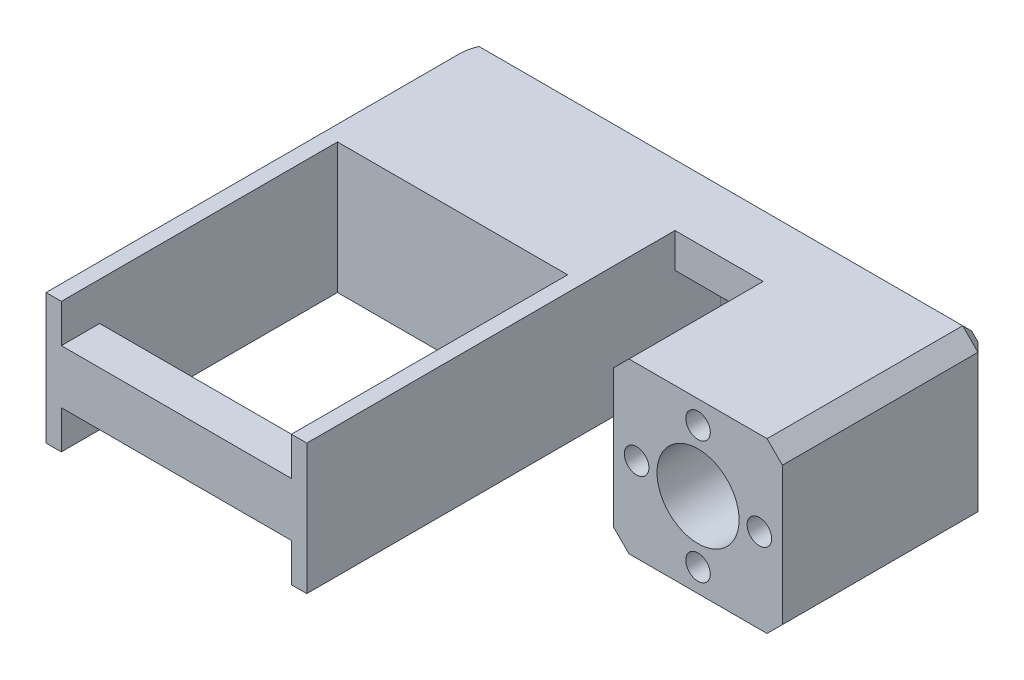
SolidWorks part; units mm, degrees
ref_plane "Płaszczyzna przednia" through (0, 0, 0) normal (0, 0, 1) x (1, 0, 0)
ref_plane "Płaszczyzna górna" through (0, 0, 0) normal (0, 1, 0) x (1, 0, 0)
ref_plane "Płaszczyzna prawa" through (0, 0, 0) normal (1, 0, 0) x (0, 0, -1)
sketch "Szkic2" plane through (0, 0, 0) normal (0, 1, 0) x (1, 0, 0)
  line L0 (0, 0) -> (0, 11.0602) construction
  line L5 (17, 19) -> (-17, 19)
  line L6 (17, 19) -> (17, -19)
  line L11 (17, -19) -> (-17, -19)
  line L12 (-17, 19) -> (-17, -19)
  line L13 (17, 19) -> (-17, -19) construction
  line L14 (17, -19) -> (-17, 19) construction
  line L16 (15, 17) -> (-15, 17)
  line L17 (15, 17) -> (15, -14)
  line L18 (15, -14) -> (-15, -14)
  line L19 (-15, 17) -> (-15, -14)
  line L20 (15, 17) -> (-15, -14) construction
  line L21 (15, -14) -> (-15, 17) construction
  point P0 (0, 0)
  point P5 (0, 1.5)
  dimension "D1" = 34
  dimension "D2" = 38
  dimension "D3" = 2
  dimension "D4" = 2
  dimension "D5" = 5
extrude "Dodanie-wyciągnięcie1" add sketch "Szkic2" along normal blind 17
sketch "Szkic6" plane through (0, 0, 14) normal (0, 0, -1) x (-1, 0, 0)
  line L0 (0, 17) -> (0, 0) construction
  line L1 (15, 17) -> (-15, 17) construction
  line L2 (15, 0) -> (-15, 0) construction
  line L3 (-15, 17) -> (-15, 0) construction
  line L4 (15, 5) -> (-15, 5)
  line L5 (15, 5) -> (15, 12)
  line L6 (15, 12) -> (-15, 12)
  line L7 (-15, 5) -> (-15, 12)
  line L8 (15, 5) -> (-15, 12) construction
  line L9 (15, 12) -> (-15, 5) construction
  line L11 (-15, 17) -> (15, 17)
  line L12 (-15, 17) -> (-15, 0)
  line L13 (-15, 0) -> (15, 0)
  line L14 (15, 17) -> (15, 0)
  point P6 (0, 8.5)
  line M9 (-15, 0) -> (15, 0)
  line M10 (15, 0) -> (15, 17)
  line M11 (15, 17) -> (-15, 17)
  line M12 (-15, 17) -> (-15, 0)
  dimension "D1" = 5
extrude "Wytnij-wyciągnięcie1" cut sketch "Szkic6" against normal blind 17 contours L6 M10 M11 M12 | L4 M10 M12 M9
sketch "Szkic7" plane through (0, 0, -19) normal (0, 0, -1) x (-1, 0, 0)
  line L1 (-17, 17) -> (17, 17)
  line L2 (-17, 17) -> (-17, 0)
  line L3 (-17, 0) -> (17, 0)
  line L4 (17, 17) -> (17, 0)
extrude "Dodanie-wyciągnięcie2" add sketch "Szkic7" along normal blind 10
sketch "Szkic8" plane through (0, 0, -29) normal (0, 0, -1) x (-1, 0, 0)
  line L0 (-17, 17) -> (-17, 18) construction
  line L1 (-17, 17) -> (-24, 17)
  line L2 (-17, 17) -> (-17, 12.5)
  line L3 (-17, 12.5) -> (-24, 12.5)
  line L4 (-24, 17) -> (-24, 12.5)
  line L5 (-17, 17) -> (17, 17)
  line L6 (-17, 17) -> (-17, 0)
  line L7 (-17, 0) -> (17, 0)
  line L8 (17, 17) -> (17, 0)
  line L9 (-17, 18) -> (-22.5, 18) construction
  line L10 (-37.5, 18) -> (-37.5, -6) construction
  line L11 (-22.5, 18) -> (-52.5, 18) construction
  line L12 (-24, 17) -> (-37.5, 17)
  line L13 (-24, 12.5) -> (-26.9837, 2.7739)
  circle A0 centre (-37.5, 6) radius 5.35
  circle A1 centre (-37.5, 6) radius 11
  line M16 (-17, 17) -> (-17, 0)
  line M17 (-17, 0) -> (17, 0)
  line M18 (17, 0) -> (17, 17)
  line M19 (17, 17) -> (-17, 17)
  dimension "D6" = 10.7
  dimension "D1" = 4.5
  dimension "D2" = 7
  dimension "D3" = 5.5
  dimension "D4" = 1
  dimension "D5" = 24
  dimension "30" = 30
extrude "Dodanie-wyciągnięcie3" add sketch "Szkic8" along normal blind 10 contours A1 A0 | A1 L13 L4 L12 | L1 L4 L3 M16 | M19 M16 M17 M18
sketch "Szkic10" plane through (0, 0, -29) normal (0, 0, 1) x (1, 0, 0)
  circle A0 centre (37.5, 6) radius 5.35
  circle A1 centre (37.5, 6) radius 11
extrude "Dodanie-wyciągnięcie4" add sketch "Szkic10" along normal blind 17.5
sketch "Szkic11" plane through (0, 0, -39) normal (0, 0, -1) x (-1, 0, 0)
  circle A0 centre (-37.5, 6) radius 4.2
  circle A1 centre (-37.5, 6) radius 5.35
  dimension "D1" = 8.4
extrude "Dodanie-wyciągnięcie5" add sketch "Szkic11" against normal blind 16
sketch "Szkic13" plane through (0, 0, -11.5) normal (0, 0, 1) x (1, 0, 0)
  line L0 (37.5, 6) -> (37.5, 14) construction
  circle A0 centre (37.5, 6) radius 8
  circle A1 centre (37.5, 14) radius 1.6
  circle A2 centre (45.5, 6) radius 1.6
  circle A3 centre (37.5, -2) radius 1.6
  circle A4 centre (29.5, 6) radius 1.6
  point P16 (37.5, 6)
  dimension "D3" = 3.2
  dimension "D1" = 8
  dimension "D2" = 4
extrude "Wytnij-wyciągnięcie2" cut sketch "Szkic13" against normal blind 10 contours A0 A4 | A0 A4 | A1 L0 A0 | A0 A1 | L0 A1 A0 | A0 A2 | A0 A2 | A0 A3 | A0 A3
sketch "Szkic16" plane through (0, 0, -39) normal (0, 0, -1) x (-1, 0, 0)
  line L0 (17, 17) -> (-37.5, 17) construction
  line L1 (-26.5, 17) -> (-48.5, 17)
  line L2 (-26.5, 17) -> (-26.5, -5)
  line L3 (-26.5, -5) -> (-48.5, -5)
  line L4 (-48.5, 17) -> (-48.5, -5)
  line L5 (-26.5, 17) -> (-48.5, -5) construction
  line L6 (-26.5, -5) -> (-48.5, 17) construction
  arc A0 (-37.5, 17) -> (-26.9837, 2.7739) centre (-37.5, 6) ccw construction
  circle A1 centre (-37.5, 6) radius 11
  point P0 (-37.5, 6)
  arc M5 (-37.5, 17) -> (-26.9837, 2.7739) centre (-37.5, 6) ccw
  line M6 (-26.9837, 2.7739) -> (-24, 12.5)
  line M11 (17, 17) -> (-37.5, 17)
extrude "Dodanie-wyciągnięcie6" add sketch "Szkic16" against normal up to surface (27.5 mm away) contours L1 L4 M5 | A1 L2 M11 | L3 L2 M6 M5 | L4 L3 M5 | A1 L2 M6 up to face at (31.1, 6, -11.5)
chamfer "Sfazowanie1" distance 2 angle 45 4 edges at (26.5, -5, -25.25) (48.5, -5, -25.25) (26.5, 17, -20.25) (48.5, 17, -25.25)
chamfer "Sfazowanie2" distance 2 angle 45 3 edges at (17, 6.25, -39) (0, 0, -39) (-17, 8.5, -39)
chamfer "Sfazowanie3" distance 2 angle 45 9 edges at (19.5, 12.5, -39) (15.75, 17, -39) (47.5, 16, -39) (48.5, 6, -39) (47.5, -4, -39) (37.5, -5, -39) (27.5, -4, -39) (26.5, 0.6753, -39) (25.25, 8.4253, -39)
fillet "Zaokrąglenie1" radius 5 2 edges at (17, 6.25, -37) (-17, 8.5, -37)
